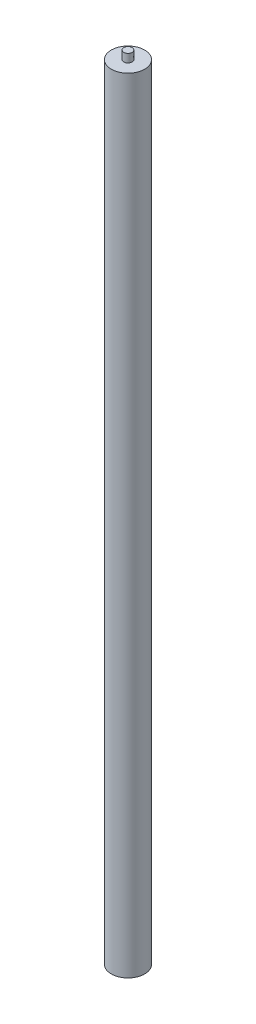
SolidWorks part; units mm, degrees
ref_plane "Front Plane" through (0, 0, 0) normal (0, 0, 1) x (1, 0, 0)
ref_plane "Top Plane" through (0, 0, 0) normal (0, 1, 0) x (1, 0, 0)
ref_plane "Right Plane" through (0, 0, 0) normal (1, 0, 0) x (0, 0, -1)
sketch "Sketch1" plane through (0, 0, 0) normal (0, 1, 0) x (1, 0, 0)
  circle A0 centre (0, 0) radius 12.7
  dimension "D1" = 25.4
extrude "Boss-Extrude1" add sketch "Sketch1" along normal blind 596.9
sketch "Sketch2" plane through (0, 596.9, 0) normal (0, 1, 0) x (-1, 0, 0)
  circle A0 centre (0, 0) radius 3.175
  dimension "D1" = 6.35
extrude "Boss-Extrude2" add sketch "Sketch2" along normal blind 6.35 and the other way blind 603.25
